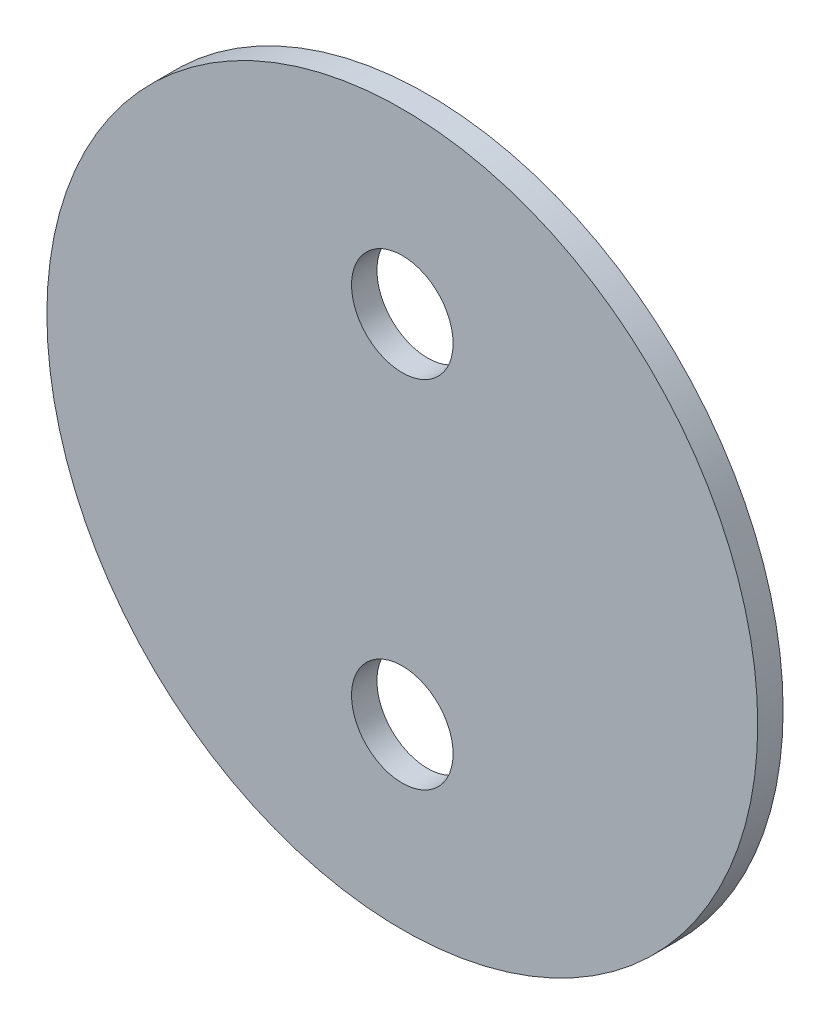
SolidWorks part; units mm, degrees
ref_plane "Płaszczyzna przednia" through (0, 0, 0) normal (0, 0, 1) x (1, 0, 0)
ref_plane "Płaszczyzna górna" through (0, 0, 0) normal (0, 1, 0) x (1, 0, 0)
ref_plane "Płaszczyzna prawa" through (0, 0, 0) normal (1, 0, 0) x (0, 0, -1)
sketch "Szkic1" plane through (0, 0, 0) normal (0, 0, 1) x (1, 0, 0)
  circle A0 centre (0, 0) radius 14
  circle A1 centre (0, 7) radius 2
  circle A3 centre (0, -7) radius 2
  dimension "D1" = 28
  dimension "D4" = 7
  dimension "D2" = 4
  dimension "D3" = 7
sketch "Szkic3" plane through (0, 0, 0) normal (1, 0, 0) x (0, 0, -1)
  line L0 (0, 0) -> (1, 0)
  dimension "D1" = 1
ref_plane "Płaszczyzna2" through (0, 0, -1) normal (0, 0, 1) x (1, 0, 0)
sketch "Szkic4" plane through (0, 0, -1) normal (0, 0, 1) x (1, 0, 0)
  line L0 (0, 0) -> (-0.2, 0)
  dimension "D1" = 0.2
sketch "Szkic5" plane through (0, 0, 0) normal (0, 1, 0) x (1, 0, 0)
  line L0 (0, 0) -> (-0.2, 1)
sweep "Wyciągnięcie po ścieżce3" add profiles "Szkic1" path "Szkic3"
